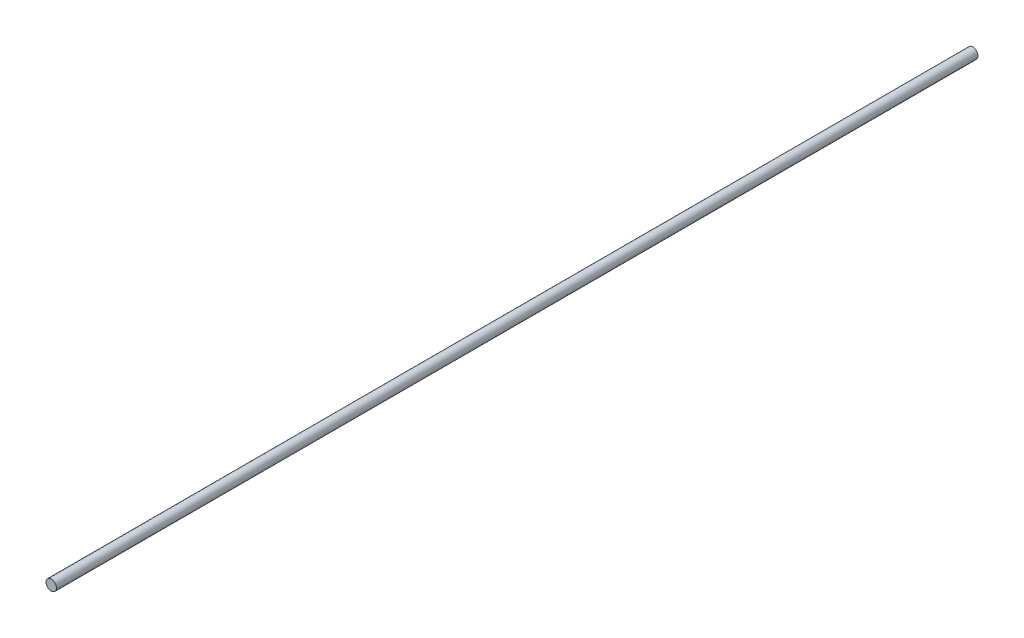
SolidWorks part; units mm, degrees
material "1060 Alloy"
ref_plane "Front Plane" through (0, 0, 0) normal (0, 0, 1) x (1, 0, 0)
ref_plane "Top Plane" through (0, 0, 0) normal (0, 1, 0) x (1, 0, 0)
ref_plane "Right Plane" through (0, 0, 0) normal (1, 0, 0) x (0, 0, -1)
sketch "Sketch2" plane through (0, 0, 0) normal (0, 0, 1) x (1, 0, 0)
  circle A0 centre (14.8073, 22.8368) radius 6.35
  dimension "D1" = 12.7
extrude "Boss-Extrude2" add sketch "Sketch2" along normal blind 1122.934 contours A0
equation "\"Force\"= 400"
equation "\"MaxDeflection\"= 0.009in"
equation "\"ElasticModulus\"= 10007603.9"
equation "\"Diameter\"= 0.50in"
equation "\"Area\"= ( pi / 4 ) * ( \"Diameter\" ) ^ 2"
equation "\"Length\"= ( \"MaxDeflection\" * \"Area\" * \"ElasticModulus\" ) / ( \"Force\" )"
